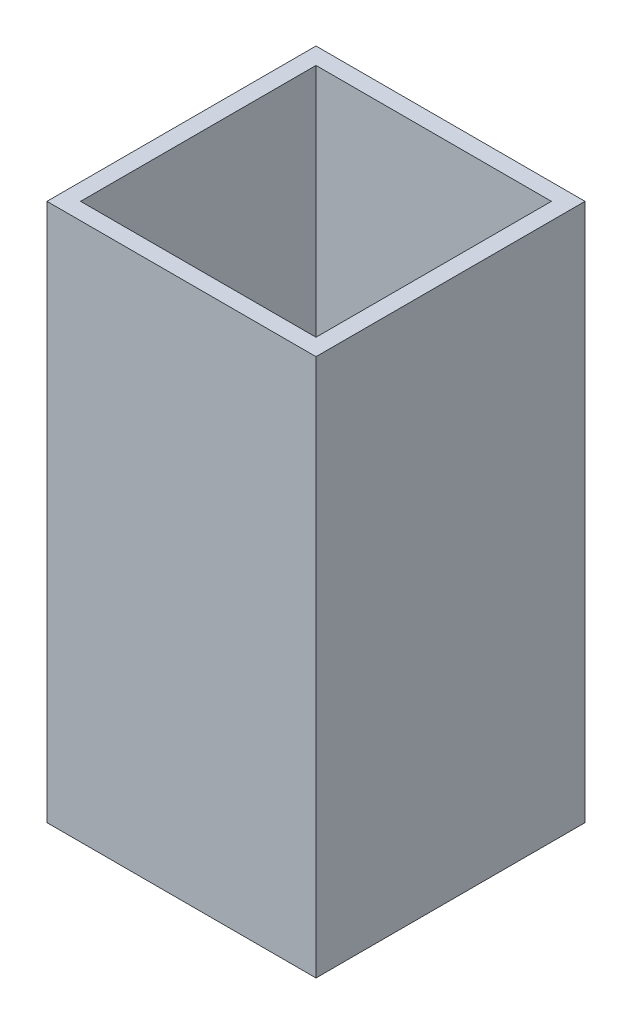
SolidWorks part; units mm, degrees
material "6061 Alloy"
ref_plane "Front Plane" through (0, 0, 0) normal (0, 0, 1) x (1, 0, 0)
ref_plane "Top Plane" through (0, 0, 0) normal (0, 1, 0) x (1, 0, 0)
ref_plane "Right Plane" through (0, 0, 0) normal (1, 0, 0) x (0, 0, -1)
sketch "Sketch1" plane through (0, 0, 0) normal (0, 1, 0) x (1, 0, 0)
  line L1 (12.7, 12.7) -> (-12.7, 12.7)
  line L2 (12.7, 12.7) -> (12.7, -12.7)
  line L3 (12.7, -12.7) -> (-12.7, -12.7)
  line L4 (-12.7, 12.7) -> (-12.7, -12.7)
  line L5 (12.7, 12.7) -> (-12.7, -12.7) construction
  line L6 (12.7, -12.7) -> (-12.7, 12.7) construction
  line L7 (11.1125, 11.1125) -> (-11.1125, 11.1125)
  line L8 (11.1125, 11.1125) -> (11.1125, -11.1125)
  line L9 (11.1125, -11.1125) -> (-11.1125, -11.1125)
  line L10 (-11.1125, 11.1125) -> (-11.1125, -11.1125)
  line L11 (11.1125, 11.1125) -> (-11.1125, -11.1125) construction
  line L12 (11.1125, -11.1125) -> (-11.1125, 11.1125) construction
  point P0 (0, 0)
  point P6 (0, 0)
  dimension "D1" = 25.4
  dimension "D2" = 25.4
  dimension "D3" = 1.5875
  dimension "D4" = 1.5875
extrude "Boss-Extrude1" add sketch "Sketch1" along normal blind 50.8
